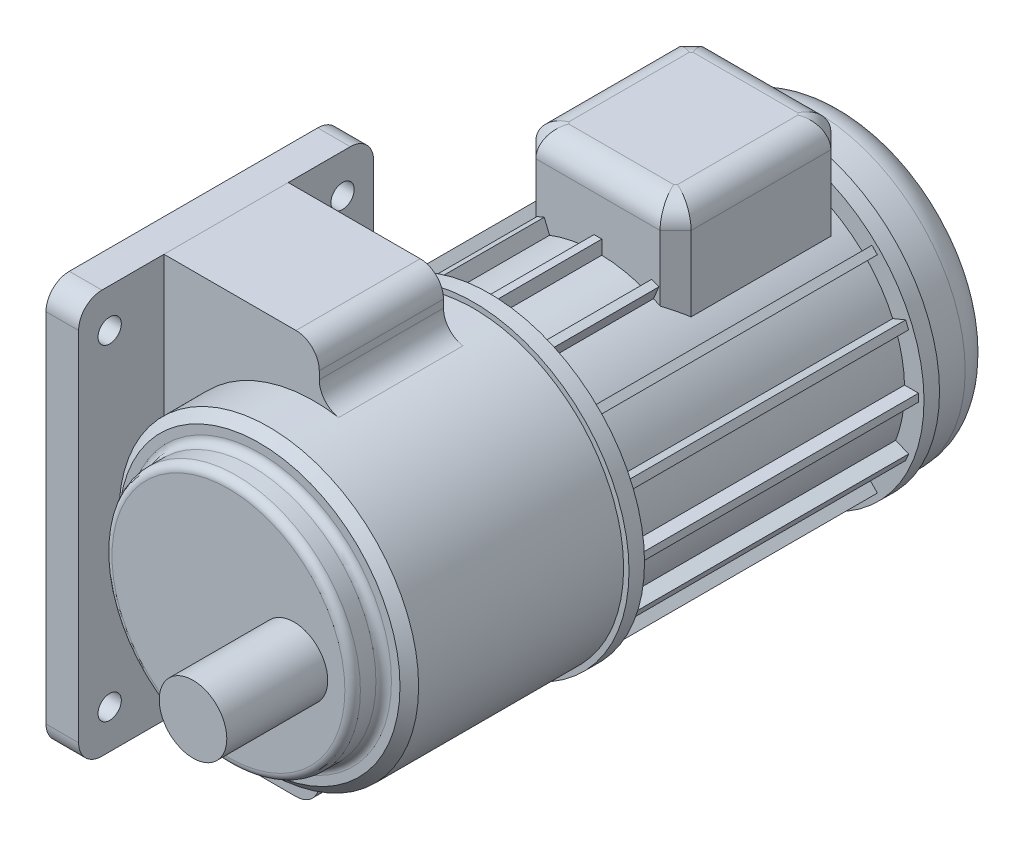
SolidWorks part; units mm, degrees
ref_plane "Alzado" through (0, 0, 0) normal (0, 0, 1) x (1, 0, 0)
ref_plane "Planta" through (0, 0, 0) normal (0, 1, 0) x (1, 0, 0)
ref_plane "Vista lateral" through (0, 0, 0) normal (1, 0, 0) x (0, 0, -1)
sketch "Sketch1" plane through (0, 0, 0) normal (0, 0, 1) x (1, 0, 0)
  circle A0 centre (0, 0) radius 96.5
  dimension "D1" = 193
extrude "Boss-Extrude1" add sketch "Sketch1" along normal blind 463
ref_plane "Plane1" through (-96.5, 0, 0) normal (-1, 0, 0) x (0, 0, 1)
sketch "Sketch2" plane through (-96.5, 0, 0) normal (-1, 0, 0) x (0, 0, 1)
  line L0 (378, 130) -> (378, -130) construction
  line L1 (398, -130) -> (208, -130)
  line L2 (398, -130) -> (398, 130)
  line L3 (398, 130) -> (208, 130)
  line L4 (208, -130) -> (208, 130)
  line L5 (398, -130) -> (208, 130) construction
  line L6 (398, 130) -> (208, -130) construction
  line L7 (228, 130) -> (228, -130) construction
  line L8 (463, -96.5) -> (463, 96.5) construction
  point P0 (303, 0)
  point P10 (303, 130)
  dimension "D1" = 190
  dimension "D2" = 260
  dimension "D3" = 150
  dimension "D4" = 75
  dimension "D5" = 85
extrude "Boss-Extrude2" add sketch "Sketch2" along normal blind 21 separate body
sketch "Sketch3" plane through (0, 0, 463) normal (0, 0, 1) x (1, 0, 0)
  circle A0 centre (42.2, 0) radius 21.75
  circle A2 centre (0, 0) radius 96.5
  circle A3 centre (0, 0) radius 96.5
  dimension "D2" = 43.5
  dimension "D1" = 42.2
  dimension "D3" = 0
extrude "Cut-Extrude1" cut sketch "Sketch3" against normal blind 65
fillet "Fillet1" radius 20 1 edges at (96.5, 0, 0)
sketch "Sketch4" plane through (0, 0, 398) normal (0, 0, 1) x (1, 0, 0)
  circle A0 centre (0, 0) radius 80
  circle A2 centre (0, 0) radius 96.5
  circle A3 centre (0, 0) radius 96.5
  dimension "D1" = 160
  dimension "D2" = 0
extrude "Cut-Extrude2" cut sketch "Sketch4" against normal blind 20
chamfer "Chamfer1" distance 6 angle 45 1 edges at (96.5, 0, 378)
fillet "Fillet2" radius 5 2 edges at (80, 0, 398) (80, 0, 378)
sketch "Sketch6" plane through (-96.5, 0, 0) normal (1, 0, 0) x (0, 0, -1)
  line L0 (-208, -130) -> (-398, -130) construction
  line L1 (-343, 130) -> (-263, 130)
  line L2 (-343, 130) -> (-343, -130)
  line L3 (-343, -130) -> (-263, -130)
  line L4 (-263, 130) -> (-263, -130)
  line L5 (-343, 130) -> (-263, -130) construction
  line L6 (-343, -130) -> (-263, 130) construction
  line L7 (-398, 130) -> (-208, 130) construction
  point P0 (-303, 0)
  point P9 (-303, 130)
  dimension "D1" = 80
extrude "Boss-Extrude6" add sketch "Sketch6" along normal blind 100
fillet "Fillet3" radius 15 4 edges at (3.5, -130, 303) (3.5, 96.4365, 303) (3.5, -96.4365, 303) (3.5, 130, 303)
ref_plane "Plane2" through (0, 0, 240) normal (0, 0, -1) x (-1, 0, 0)
sketch "Sketch7" plane through (0, 0, 240) normal (0, 0, -1) x (-1, 0, 0)
  circle A0 centre (0, 0) radius 96.5 construction
  circle A1 centre (0, 0) radius 96.5
  circle A2 centre (0, 0) radius 87.5
  dimension "D1" = 175
extrude "Cut-Extrude3" cut sketch "Sketch7" along normal blind 200
sketch "Sketch8" plane through (0, 0, 240) normal (0, 0, -1) x (-1, 0, 0)
  line L1 (-78.5324, -2.5) -> (-96.4676, -2.5)
  line L2 (-78.5324, -2.5) -> (-78.5324, 2.5)
  line L3 (-78.5324, 2.5) -> (-96.4676, 2.5)
  line L4 (-96.4676, -2.5) -> (-96.4676, 2.5)
  line L5 (-78.5324, -2.5) -> (-96.4676, 2.5) construction
  line L6 (-78.5324, 2.5) -> (-96.4676, -2.5) construction
  circle A0 centre (0, 0) radius 87.5 construction
  circle A1 centre (0, 0) radius 96.5 construction
  point P0 (-87.5, 0)
  point P9 (-87.4763, 2.0349)
  dimension "D1" = 5
extrude "Boss-Extrude7" add sketch "Sketch8" along normal up to surface (200 mm away) up to face at (-96.5, 0, 40)
pattern_circular "CirPattern1" count 16 over 360 about axis through (0, 0, 0) along (0, 0, 1) of "Boss-Extrude7"
sketch "Sketch9" plane through (0, 0, 0) normal (0, 1, 0) x (1, 0, 0)
  line L1 (-50, -160) -> (50, -160)
  line L2 (-50, -160) -> (-50, -50)
  line L3 (-50, -50) -> (50, -50)
  line L4 (50, -160) -> (50, -50)
  line L5 (-50, -160) -> (50, -50) construction
  line L6 (-50, -50) -> (50, -160) construction
  point P0 (0, -105)
  point P5 (0, -50)
  dimension "D1" = 100
  dimension "D2" = 110
  dimension "D3" = 50
extrude "Boss-Extrude8" add sketch "Sketch9" along normal blind 135
chamfer "Chamfer2" distance 10 angle 45 4 edges at (50, 103.4035, 50) (50, 103.4035, 160) (-50, 103.4035, 160) (-50, 103.4035, 50)
fillet "Fillet4" radius 15 8 edges at (45, 135, 155) (0, 135, 160) (-45, 135, 155) (-50, 135, 105) (-45, 135, 55) (0, 135, 50) (45, 135, 55) (50, 135, 105)
fillet "Fillet5" radius 15 4 edges at (-107, -130, 398) (-107, -130, 208) (-107, 130, 398) (-107, 130, 208)
hole_wizard "Ø16.0 mm Dowel Holes1" positions "Sketch10" profile "Sketch11" hole size "Ø16.0" standard "ANSI Metric"
sketch "Sketch10" plane through (-117.5, 0, 0) normal (-1, 0, 0) x (0, 0, 1)
  line L1 (383, 130) -> (223, 130) construction
  point P0 (228, 105)
  point P2 (378, 105)
  point P4 (378, -105)
  point P6 (228, -105)
  point P14 (303, 130)
  point P15 (0, 0)
  point P16 (0, 0)
  point P17 (0, 0)
  point P18 (0, 0)
  point P19 (378, -105)
  dimension "D1" = 150
  dimension "D2" = 210
  dimension "D3" = 105
  dimension "D4" = 75
sketch "Sketch11" plane through (-117.5, 105, 228) normal (0, 1, 0) x (0, 0, 1)
  line L0 (0, 0) -> (0, 34.5065)
  line L1 (0, 34.5065) -> (7.5, 30)
  line L2 (7.5, 30) -> (7.5, 0)
  line L5 (7.5, 0) -> (0, 0)
  line L10 (0, 34.5065) -> (-7.5, 30) construction
  line L11 (0, -6.35) -> (0, 107.95) construction
  dimension "Hole Dia." = 15
  dimension "Hole Depth" = 30
  dimension "Drill Angle" = 118
sketch "Sketch12" plane through (0, 0, 240) normal (0, 0, -1) x (-1, 0, 0)
  circle A0 centre (0, 0) radius 100
  dimension "D1" = 200
extrude "Boss-Extrude11" add sketch "Sketch12" along normal blind 10 separate body
sketch "Sketch13" plane through (0, 0, 40) normal (0, 0, 1) x (1, 0, 0)
  circle A1 centre (0, 0) radius 100
  circle A2 centre (0, 0) radius 100
  dimension "D1" = 0
extrude "Boss-Extrude12" add sketch "Sketch13" along normal blind 10
